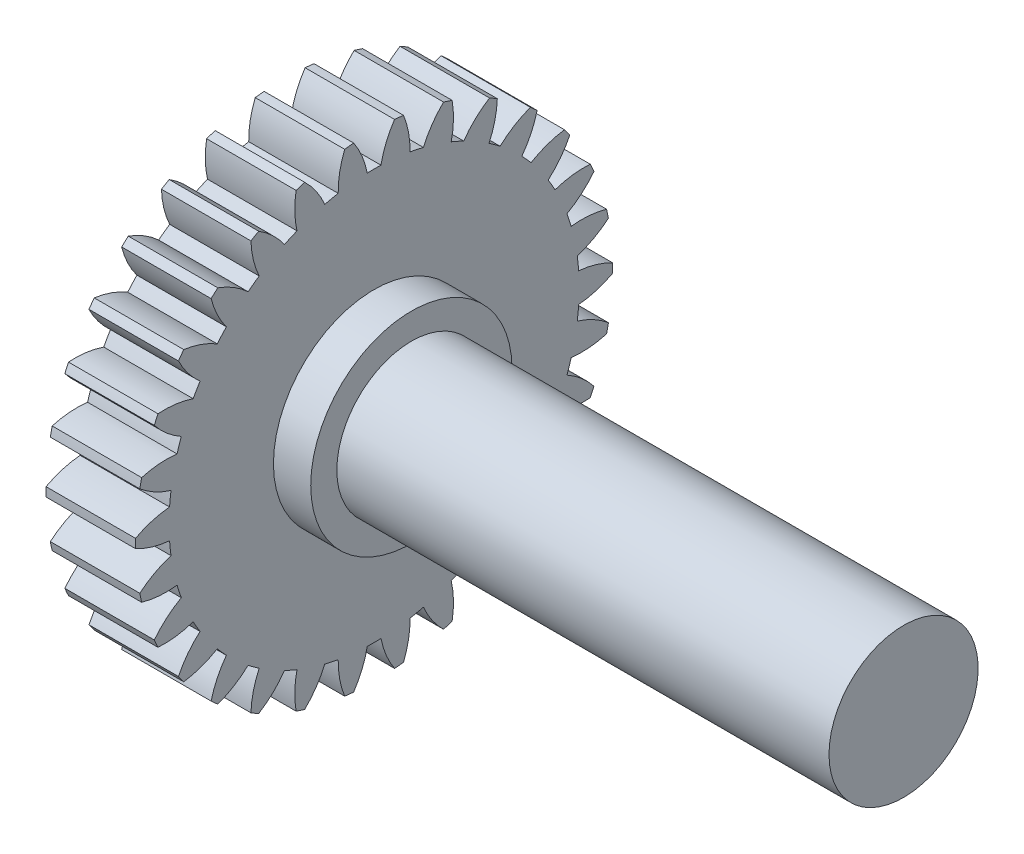
SolidWorks part; units mm, degrees
ref_plane "Plane1" through (0, 0, 0) normal (0, 0, 1) x (1, 0, 0)
ref_plane "Plane2" through (0, 0, 0) normal (0, 1, 0) x (1, 0, 0)
ref_plane "Plane3" through (0, 0, 0) normal (1, 0, 0) x (0, 0, -1)
sketch "HoldingSke" plane through (0, 0, 0) normal (0, 1, 0) x (1, 0, 0)
  line L0 (0, 0) -> (0.433, -0.25)
  line L1 (-15, 0) -> (100, 0) construction
  line L2 (0, 0) -> (-2.1039, 2.3779)
  line L3 (0, 0) -> (-11.863, 4.5341)
  line L4 (0, 0) -> (7.479, 4.318)
  line L5 (0, 0) -> (-46.8476, -17.4728)
  line L6 (0, 0) -> (-9.9476, -6.7116)
  line L7 (-2.1039, 2.3779) -> (8.6586, 51.2059)
  line L8 (-76.2, 54.61) -> (-73.4, 54.61)
  line L9 (-71.009, 38.7566) -> (-53.1078, 45.2721)
  line L10 (-76.2, 71.12) -> (104.1128, 71.12)
  line L11 (0, 0) -> (-12, 0)
  line L12 (-76.2, 101.6) -> (-76.133, 101.6)
  line L13 (24.9733, 27.94) -> (52.9518, 28.4284)
  line L14 (24.9733, 27.94) -> (24.9743, 27.94)
  line L15 (24.9733, 27.94) -> (100.4006, 29.5858)
  line L16 (-63.627, -2) -> (-12.827, -2)
  circle A0 centre (0, 0) radius 10
  circle A1 centre (0, 0) radius 27.499
  circle A2 centre (0, 0) radius 37.5
  circle A3 centre (0, 0) radius 10
  dimension "MHD" = 54.998
  dimension "Hub_dia" = 75
  dimension "Bore" = 20
  dimension "MBD" = 20
  dimension "Num_teeth" = 30
  dimension "Pitch" = 0.5
  dimension "Overall_len" = 50
  dimension "Show_teeth" = 30
  dimension "Thickness" = 12
  dimension "OAL" = 50.0001
  dimension "T_dim" = 2.8
  dimension "Ap" = 20
  dimension "H" = 19.05
  dimension "Pitch_radius" = 180.3128
  dimension "Width" = 12
  dimension "Backlash" = 0.067
  dimension "Addendum_fac" = 1
  dimension "Dedendum_fac" = 1.25
  dimension "Clearance_fac" = 0.25
  dimension "Dedendum_add" = 0.001
  dimension "Module" = 2
sketch "BasProSke" plane through (0, 0, 0) normal (0, 1, 0) x (1, 0, 0)
  line L0 (-10, 0) -> (60, 0) construction
  line L1 (0, 0) -> (0, 32)
  line L2 (0, 0) -> (12, 0)
  line L3 (12, 0) -> (12, 32)
  line L4 (12, 32) -> (0, 32)
  dimension "Thickness" = 12
  dimension "Diameter" = 64
revolve "Base-Revolve" add sketch "BasProSke" angle 360 about L0
sketch "TooCutSke" plane through (0, 0, 0) normal (1, 0, 0) x (0, 0, -1)
  line L1 (0, 0) -> (0, 107) construction
  line L2 (0, 0) -> (-1.6873, 29.9525) construction
  line L3 (0, 0) -> (-6.2643, 59.6013) construction
  line L4 (-1.6873, 29.9525) -> (-3.1322, 29.8007) construction
  arc A0 (0.9186, 27.4837) -> (-0.9186, 27.4837) centre (0, 0) ccw
  arc A1 (2.7618, 31.9061) -> (-2.7618, 31.9061) centre (0, 0) ccw
  circle A2 centre (0, 0) radius 30 construction
  circle A3 centre (0, 0) radius 28.1908 construction
  arc A4 (-0.9186, 27.4837) -> (-2.7618, 31.9061) centre (-12.6936, 25.1712) ccw
  arc A5 (2.7618, 31.9061) -> (0.9186, 27.4837) centre (12.6936, 25.1712) ccw
  dimension "Root_dia" = 54.998
  dimension "Overcut_dia" = 64.0508
  dimension "Pitch_dia" = 60
  dimension "Base_dia" = 56.3816
  dimension "Flank_rad" = 12
  dimension "Half_ang" = 6
  dimension "Half_CT" = 1.4528
extrude "ToothCut" cut sketch "TooCutSke" along normal through all
fillet "Breaks" [suppressed] radius 0.04
fillet "RootFillets" [suppressed] radius 0.501
pattern_circular "TeethCuts" count 30 every 12 about axis through (-10, 0, 0) along (1, 0, 0) of "ToothCut", "RootFillets", "Breaks"
sketch "HubNeaOneSke" plane through (0, 0, 0) normal (-1, 0, 0) x (0, 0, 1)
  circle A0 centre (0, 0) radius 27.499
  dimension "Diameter" = 54.998
extrude "HubNearOne" [suppressed] add sketch "HubNeaOneSke" along normal blind 38.0001
sketch "HubNeaBotSke" plane through (0, 0, 0) normal (-1, 0, 0) x (0, 0, 1)
  circle A0 centre (0, 0) radius 27.499
  dimension "Diameter" = 54.998
extrude "HubNearBoth" [suppressed] add sketch "HubNeaBotSke" along normal blind 19
ref_plane "FarPln" through (12, 0, 0) normal (1, 0, 0) x (0, 0, -1)
sketch "HubFarSke" plane through (12, 0, 0) normal (1, 0, 0) x (0, 0, -1)
  circle A0 centre (0, 0) radius 27.499
  dimension "Diameter" = 54.998
extrude "HubFar" [suppressed] add sketch "HubFarSke" along normal blind 19
sketch "BorSke" plane through (0, 0, 0) normal (1, 0, 0) x (0, 0, -1)
  circle A0 centre (0, 0) radius 10
  dimension "Diameter" = 20
extrude "Bore" cut sketch "BorSke" along normal mid plane 100.0001
sketch "KeySke" plane through (0, 0, 0) normal (1, 0, 0) x (0, 0, -1)
  line L0 (-3, 0) -> (-3, 12.8)
  line L1 (-3, 12.8) -> (3, 12.8)
  line L2 (3, 12.8) -> (3, 0)
  line L3 (0, 0) -> (0, 34) construction
  line L4 (-3, 0) -> (3, 0)
  dimension "Offset" = 12.8
  dimension "Width" = 6
extrude "Keyway" [suppressed] cut sketch "KeySke" along normal mid plane 100.0001
pattern_circular "Keyway2" [suppressed] count 2 every 90 about axis through (-10, 0, 0) along (1, 0, 0)
sketch "Sketch1" plane through (0, 0, 0) normal (-1, 0, 0) x (0, 0, 1)
  circle A0 centre (0, 0) radius 10
extrude "Boss-Extrude1" add sketch "Sketch1" against normal blind 83
sketch "Sketch3" plane through (12, 0, 0) normal (1, 0, 0) x (0, 0, -1)
  circle A0 centre (0, 0) radius 13.5
extrude "Boss-Extrude2" add sketch "Sketch3" along normal blind 5
draft "Draft2" type of draft neutral plane draft angle 5 faces to draft 120 parameters "D1"=5
equation "' \"Module@HoldingSke\" = 6.35"
equation "' \"Num_teeth@HoldingSke\" = 12"
equation "' \"Ap@HoldingSke\" =  20"
equation "' \"Ap@HoldingSke\" = 20"
equation "' \"Width@HoldingSke\" = 0.5 * 25.4"
equation "' \"Hub_dia@HoldingSke\"= 1 * 25.4"
equation "' \"Hub_dia@HoldingSke\" = 1 * 25.4"
equation "' \"Overall_len@HoldingSke\" = 1.0 * 25.4"
equation "' \"Bore@HoldingSke\" = 0.75 * 25.4"
equation "' \"T_dim@HoldingSke\" = 0.1 * 25.4"
equation "' \"Width@KeySke\" = 0.25 * 25.4"
equation "' \"Show_teeth@HoldingSke\" = 13"
equation "' \"Backlash@HoldingSke\" = 0.009 * 25.4"
equation "' \"Addendum_fac@HoldingSke\" = 1.0"
equation "' \"Dedendum_fac@HoldingSke\" = 1.25"
equation "' \"Dedendum_add@HoldingSke\" = 0.00005 * 25.4"
equation "' \"Clearance_fac@HoldingSke\" = 0.25"
equation "\"Pitch@HoldingSke\" = 1 / \"Module@HoldingSke\""
equation "\"Overcut_dia@TooCutSke\" = (\"Num_teeth@HoldingSke\" + 2 * \"Addendum_fac@HoldingSke\") / \"Pitch@HoldingSke\" + 0.002 * 25.4"
equation "\"Pitch_dia@TooCutSke\" = \"Num_teeth@HoldingSke\" / \"Pitch@HoldingSke\""
equation "\"Base_dia@TooCutSke\" = \"Num_teeth@HoldingSke\" / \"Pitch@HoldingSke\" * cos((\"Ap@HoldingSke\"  * 3.14159265 / 180))"
equation "\"Root_dia@TooCutSke\" = (\"Num_teeth@HoldingSke\" + 2) / \"Pitch@HoldingSke\" - 2 * (\"Addendum_fac@HoldingSke\" + \"Dedendum_fac@HoldingSke\") / \"Pitch@HoldingSke\" - \"Dedendum_add@HoldingSke\" * 2"
equation "\"Half_ang@TooCutSke\" = 180 / \"Num_teeth@HoldingSke\""
equation "\"Half_CT@TooCutSke\" = \"Num_teeth@HoldingSke\" / \"Pitch@HoldingSke\" * sin((3.14159265 / 2 / \"Num_teeth@HoldingSke\")) / 2 - 7 * \"Backlash@HoldingSke\" / 4"
equation "\"Flank_rad@TooCutSke\" = \"Num_teeth@HoldingSke\" / \"Pitch@HoldingSke\" / 5"
equation "\"Radius@RootFillets\" = \"Clearance_fac@HoldingSke\" / \"Pitch@HoldingSke\" + \"Dedendum_add@HoldingSke\""
equation "\"Break_rad@Breaks\" = 0.02 / \"Pitch@HoldingSke\""
equation "\"Thickness@HoldingSke\" = \"Width@HoldingSke\""
equation "\"OAL@HoldingSke\" = \"Thickness@HoldingSke\""
equation "\"MHD@HoldingSke\" = (\"Num_teeth@HoldingSke\" + 2) / \"Pitch@HoldingSke\" - 2 * (\"Addendum_fac@HoldingSke\" + \"Dedendum_fac@HoldingSke\")  / \"Pitch@HoldingSke\" - \"Dedendum_add@HoldingSke\" * 2"
equation "\"MBD@HoldingSke\" = (\"Num_teeth@HoldingSke\" + 2) / \"Pitch@HoldingSke\" - 2 * (\"Addendum_fac@HoldingSke\" + \"Dedendum_fac@HoldingSke\")  / \"Pitch@HoldingSke\" - \"Dedendum_add@HoldingSke\" * 2 - 0.002 * 25.4"
equation "\"MHD@HoldingSke\" = ((sgn( \"MHD@HoldingSke\" - \"Hub_dia@HoldingSke\" )-1)*( \"MHD@HoldingSke\" - \"Hub_dia@HoldingSke\" ))/-2+ \"Hub_dia@HoldingSke\""
equation "\"MBD@HoldingSke\" = ((sgn( \"MBD@HoldingSke\" - \"Bore@HoldingSke\" )-1)*( \"MBD@HoldingSke\" - \"Bore@HoldingSke\" ))/-2+ \"Bore@HoldingSke\""
equation "\"OAL@HoldingSke\" = ((sgn( \"OAL@HoldingSke\" - \"Overall_len@HoldingSke\" )+1)*( \"OAL@HoldingSke\" - \"Overall_len@HoldingSke\" ))/2 + \"Overall_len@HoldingSke\" + 0.000002 * 25.4"
equation "\"Num_teeth@TeethCuts\" = int( \"Show_teeth@HoldingSke\" ) + 1"
equation "\"Num_teeth@TeethCuts\" = ((sgn( \"Num_teeth@TeethCuts\" - \"Num_teeth@HoldingSke\" )-1)*( \"Num_teeth@TeethCuts\" - \"Num_teeth@HoldingSke\" ))/-2+ \"Num_teeth@HoldingSke\""
equation "\"Num_teeth@TeethCuts\" = ((sgn( \"Num_teeth@TeethCuts\" - 2.0)+1)*( \"Num_teeth@TeethCuts\" - 2.0))/2 +2.0"
equation "\"Angle@TeethCuts\" = 360.0 / \"Num_teeth@HoldingSke\""
equation "\"Diameter@BasProSke\" = (\"Num_teeth@HoldingSke\" + 2 * \"Addendum_fac@HoldingSke\") / \"Pitch@HoldingSke\""
equation "\"Thickness@BasProSke\"  = \"Thickness@HoldingSke\""
equation "' \"Fillet_rad@BasProSke\" =  \"Thickness@HoldingSke\" * 0.05"
equation "' \"Fillet_rad@BasProSke\" = \"Thickness@HoldingSke\" * 0.05"
equation "\"MHD@HoldingSke\" = ((sgn( \"MHD@HoldingSke\" - \"Root_dia@TooCutSke\" )-1)*( \"MHD@HoldingSke\" - \"Root_dia@TooCutSke\" ))/-2+ \"Root_dia@TooCutSke\""
equation "\"Diameter@HubNeaOneSke\" = \"MHD@HoldingSke\""
equation "\"Length@HubNearOne\" = \"OAL@HoldingSke\" - \"Thickness@BasProSke\""
equation "\"Diameter@HubNeaBotSke\" = \"MHD@HoldingSke\""
equation "\"Length@HubNearBoth\" = ( \"OAL@HoldingSke\" - \"Thickness@BasProSke\" ) / 2.0"
equation "\"Thickness@FarPln\" = \"Thickness@BasProSke\""
equation "\"Diameter@HubFarSke\" = \"MHD@HoldingSke\""
equation "\"Length@HubFar\" = ( \"OAL@HoldingSke\" - \"Thickness@BasProSke\" ) / 2.0"
equation "\"Diameter@BorSke\" = \"MBD@HoldingSke\""
equation "\"D1@Bore\" = \"OAL@HoldingSke\" * 2.0"
equation "\"D1@Keyway\" = \"OAL@HoldingSke\" * 2.0"
equation "\"Offset@KeySke\" = \"T_dim@HoldingSke\" + \"MBD@HoldingSke\" / 2.0"
